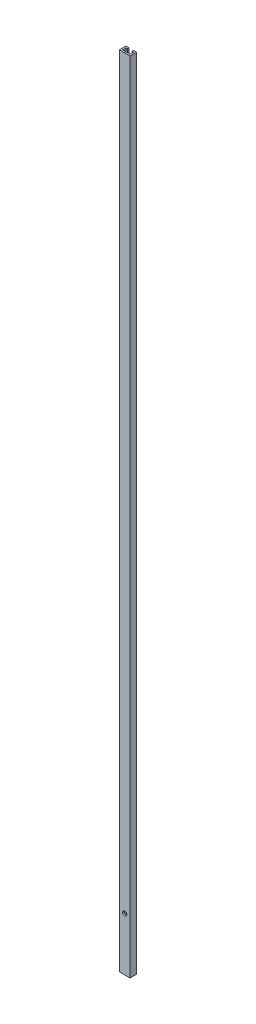
SolidWorks part; units mm, degrees
ref_plane "前视基准面" through (0, 0, 0) normal (0, 0, 1) x (1, 0, 0)
ref_plane "上视基准面" through (0, 0, 0) normal (0, 1, 0) x (1, 0, 0)
ref_plane "右视基准面" through (0, 0, 0) normal (1, 0, 0) x (0, 0, -1)
sketch "草图1" plane through (0, 0, 0) normal (0, 1, 0) x (1, 0, 0)
  line L0 (0, -5) -> (8, -5)
  line L1 (8, -5) -> (8, 0)
  line L2 (8, 0) -> (5.75, 0)
  line L3 (5.75, 0) -> (5.75, -1.15)
  line L4 (5.75, -1.15) -> (6.85, -1.15)
  line L5 (6.85, -1.15) -> (6.85, -3.85)
  line L6 (6.85, -3.85) -> (1.15, -3.85)
  line L7 (1.15, -3.85) -> (1.15, -1.15)
  line L8 (1.15, -1.15) -> (2.25, -1.15)
  line L9 (2.25, -1.15) -> (2.25, 0)
  line L10 (2.25, 0) -> (0, 0)
  line L11 (0, 0) -> (0, -5)
  line L12 (4, -3.85) -> (4, -5) construction
  line L13 (2.25, 0) -> (5.75, 0) construction
  line L14 (4, 0) -> (4, -3.85) construction
  dimension "D1" = 5
  dimension "D2" = 8
  dimension "D3" = 1.15
  dimension "D4" = 1.15
  dimension "D5" = 1.15
  dimension "D6" = 3.5
  dimension "D7" = 5.7
extrude "凸台-拉伸1" add sketch "草图1" along normal blind 600
sketch "草图2" plane through (0, 0, 5) normal (0, 0, 1) x (1, 0, 0)
  line L0 (0, 0) -> (8, 0) construction
  line L1 (4, 40) -> (4, 0) construction
  line L2 (0, 600) -> (8, 600) construction
  circle A0 centre (4, 40) radius 1.6
  dimension "D2" = 3.2
  dimension "D1" = 560
extrude "切除-拉伸1" cut sketch "草图2" against normal up to surface (1.15 mm away) up to face at (4, 300, 3.85)
